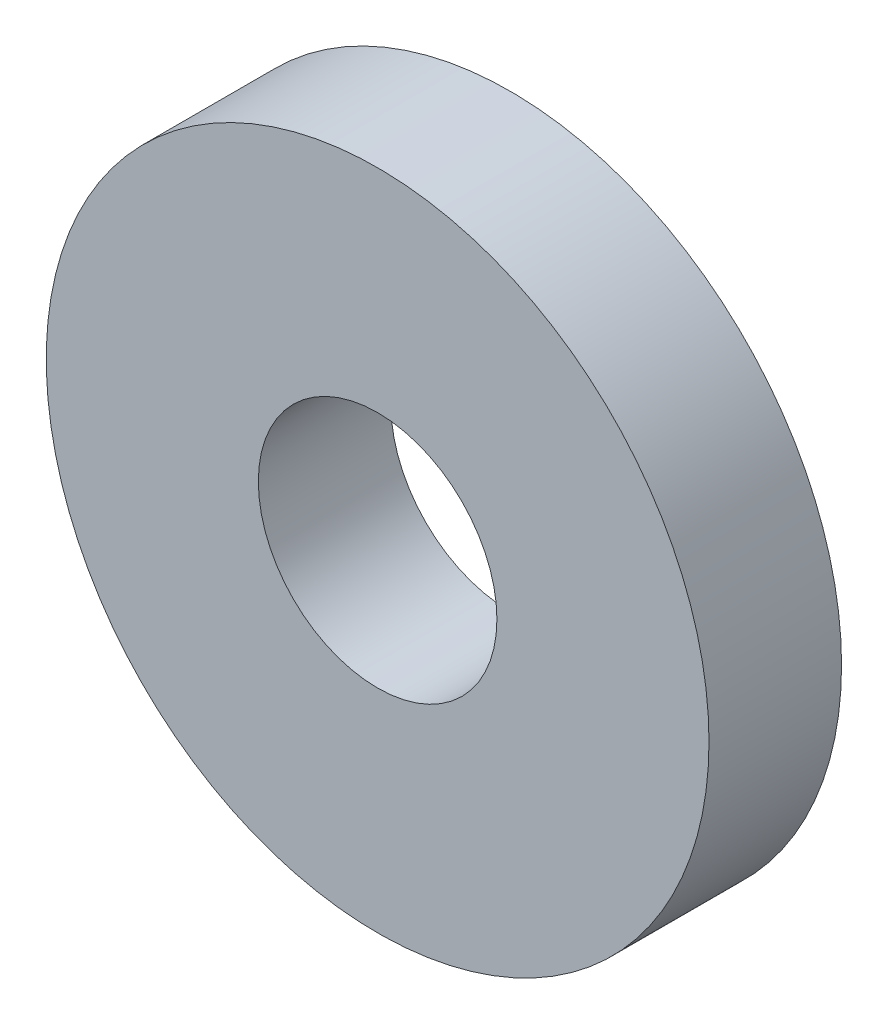
SolidWorks part; units mm, degrees
ref_plane "Спереди" through (0, 0, 0) normal (0, 0, 1) x (1, 0, 0)
ref_plane "Сверху" through (0, 0, 0) normal (0, 1, 0) x (1, 0, 0)
ref_plane "Справа" through (0, 0, 0) normal (1, 0, 0) x (0, 0, -1)
sketch "Эскиз1" plane through (0, 0, 0) normal (0, 0, 1) x (1, 0, 0)
  circle A0 centre (0, 0) radius 1.8
  circle A1 centre (0, 0) radius 5
  dimension "D1" = 3.6
  dimension "D2" = 10
extrude "Бобышка-Вытянуть1" add sketch "Эскиз1" along normal blind 2
